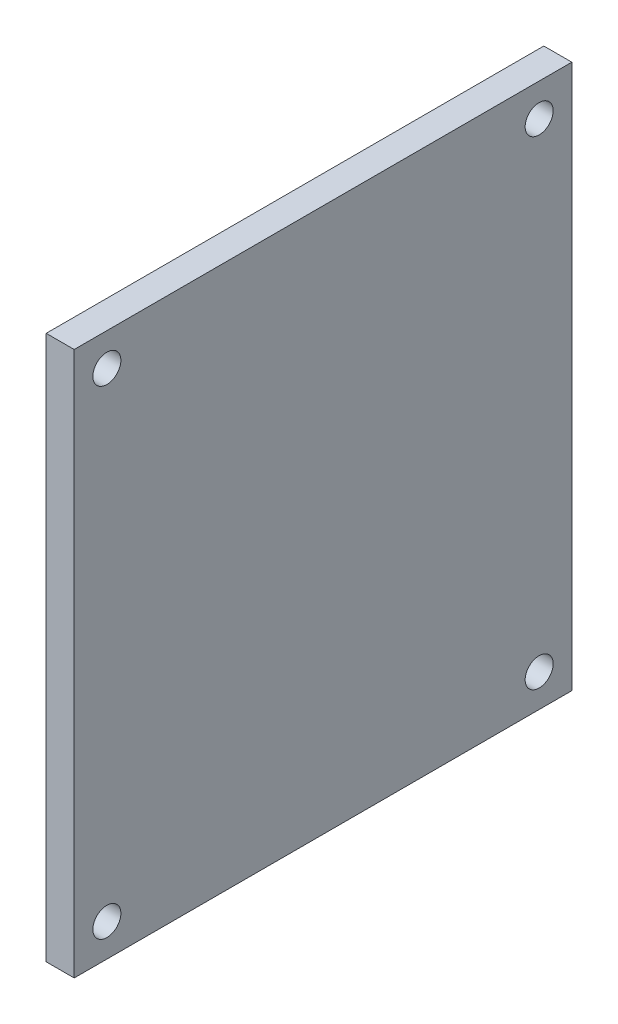
SolidWorks part; units mm, degrees
ref_plane "Front Plane" through (0, 0, 0) normal (0, 0, 1) x (1, 0, 0)
ref_plane "Top Plane" through (0, 0, 0) normal (0, 1, 0) x (1, 0, 0)
ref_plane "Right Plane" through (0, 0, 0) normal (1, 0, 0) x (0, 0, -1)
sketch "Sketch2" plane through (0, 0, 0) normal (1, 0, 0) x (0, 0, -1)
  line L1 (0, 0) -> (53.3, 0)
  line L2 (0, 0) -> (0, 58.3)
  line L3 (0, 58.3) -> (53.3, 58.3)
  line L4 (53.3, 0) -> (53.3, 58.3)
  dimension "D1" = 53.3
  dimension "D2" = 58.3
extrude "Boss-Extrude1" add sketch "Sketch2" along normal blind 3 contours L3 L4 L1 L2
hole_wizard "Ø3.0mm Dowel Hole1" positions "Sketch3" profile "Sketch4" hole size "Ø3.0" standard "ANSI Metric" end condition up to next
sketch "Sketch3" plane through (3, 0, 0) normal (1, 0, 0) x (0, 0, -1)
  line L0 (0, 58.3) -> (53.3, 58.3) construction
  line L1 (0, 0) -> (0, 58.3) construction
  line L2 (53.3, 0) -> (53.3, 58.3) construction
  line L3 (0, 0) -> (53.3, 0) construction
  point P0 (3.5, 54.8)
  point P2 (49.8, 54.8)
  point P4 (49.8, 3.5)
  point P6 (3.5, 3.5)
  dimension "D1" = 3.5
  dimension "D2" = 3.5
  dimension "D3" = 3.5
  dimension "D4" = 3.5
  dimension "D5" = 3.5
  dimension "D6" = 3.5
  dimension "D7" = 3.5
  dimension "D8" = 3.5
sketch "Sketch4" plane through (3, 54.8, -3.5) normal (0, 1, 0) x (0, 0, -1)
  line L0 (0, 0) -> (0, 3)
  line L1 (0, 3) -> (1.5, 3)
  line L2 (1.5, 3) -> (1.5, 0)
  line L5 (1.5, 0) -> (0, 0)
  line L11 (0, -6.35) -> (0, 107.95) construction
  dimension "Thru Hole Dia." = 3
  dimension "Thru Hole Depth" = 3
ref_plane "Plane1" through (0, 0, -26.65) normal (0, 0, 1) x (1, 0, 0)
